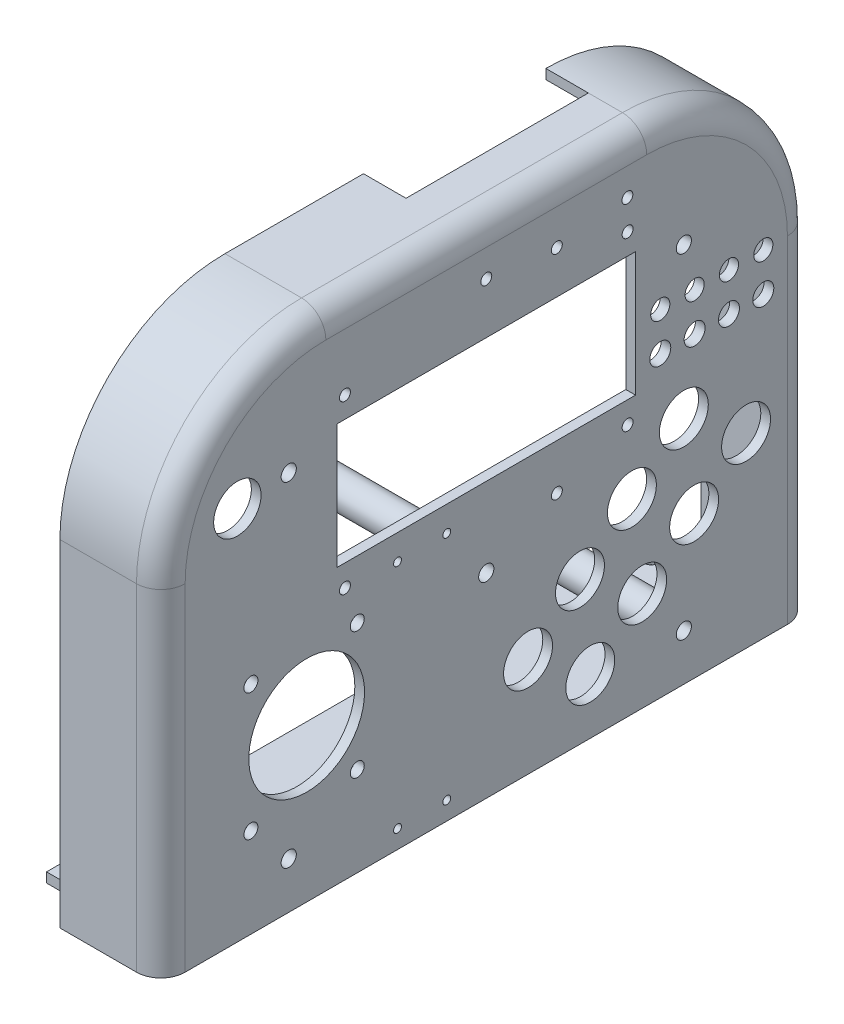
SolidWorks part; units mm, degrees
ref_plane "Front Plane" through (0, 0, 0) normal (0, 0, 1) x (1, 0, 0)
ref_plane "Top Plane" through (0, 0, 0) normal (0, 1, 0) x (1, 0, 0)
ref_plane "Right Plane" through (0, 0, 0) normal (1, 0, 0) x (0, 0, -1)
sketch "Sketch1" plane through (0, 0, 0) normal (1, 0, 0) x (0, 0, -1)
  line L0 (-107.09, -0.1) -> (107.09, -0.1) construction
  line L1 (-49.1, -20.45) -> (49.1, -20.45)
  line L2 (-49.1, -20.45) -> (-49.1, 20.45)
  line L3 (-49.1, 20.45) -> (49.1, 20.45)
  line L4 (49.1, -20.45) -> (49.1, 20.45)
  line L5 (-49.1, -20.45) -> (49.1, 20.45) construction
  line L6 (-49.1, 20.45) -> (49.1, -20.45) construction
  line L11 (-49.1, 29.95) -> (49.1, 29.95) construction
  line L12 (-49.1, 29.95) -> (-49.1, -30.15) construction
  line L13 (-49.1, -30.15) -> (49.1, -30.15) construction
  line L14 (49.1, 29.95) -> (49.1, -30.15) construction
  line L15 (-49.1, 20.45) -> (-82.6403, 20.45) construction
  line L16 (0, 0) -> (0, -0.1) construction
  line L17 (-46.5, -27.6) -> (46.5, -27.6) construction
  line L18 (-46.5, -27.6) -> (-46.5, 27.4) construction
  line L19 (-46.5, 27.4) -> (46.5, 27.4) construction
  line L20 (46.5, -27.6) -> (46.5, 27.4) construction
  line L21 (-46.5, -27.6) -> (46.5, 27.4) construction
  line L22 (-46.5, 27.4) -> (46.5, -27.6) construction
  line L23 (47.911, -49.4394) -> (85.4788, -49.4394) construction
  line L24 (65, -35.1) -> (85.4788, -49.4394) construction
  line L25 (47.911, -49.4394) -> (65, -35.1) construction
  line L26 (0, -0.1) -> (-71.6, -0.1) construction
  line L31 (0, -110.8) -> (0, 54.2) construction
  line L32 (-52.79, 54.2) -> (52.79, 54.2)
  line L33 (-59.95, -60.45) -> (-59.1, -60.45) construction
  line L34 (-42.45, -81.35) -> (-77.45, -81.35) construction
  line L35 (-42.45, -81.35) -> (-42.45, -39.55) construction
  line L36 (-42.45, -39.55) -> (-77.45, -39.55) construction
  line L37 (-77.45, -81.35) -> (-77.45, -39.55) construction
  line L38 (-42.45, -81.35) -> (-77.45, -39.55) construction
  line L39 (-42.45, -39.55) -> (-77.45, -81.35) construction
  line L40 (-107.09, -0.1) -> (-107.09, -110.8)
  line L41 (-107.09, -110.8) -> (107.09, -110.8)
  line L42 (107.09, -0.1) -> (107.09, -110.8)
  line L43 (0, -40.5) -> (0, -46.55) construction
  line L45 (-65, -95.5) -> (65, -95.5) construction
  line L46 (-65, -95.5) -> (-65, 14.5) construction
  line L47 (-65, 14.5) -> (65, 14.5) construction
  line L48 (65, -95.5) -> (65, 14.5) construction
  line L49 (-65, -95.5) -> (65, 14.5) construction
  line L50 (-65, 14.5) -> (65, -95.5) construction
  line L51 (46.42, 54.2) -> (46.42, 37.2) construction
  line L52 (0, 37.2) -> (46.42, 37.2) construction
  line L53 (23.21, 37.2) -> (23.21, -27.6) construction
  line L54 (-42.45, -81.35) -> (0, -81.35) construction
  line L56 (-29.2, -28.8) -> (-13, -28.8) construction
  line L58 (-29.2, -104.8) -> (-13, -104.8) construction
  line L59 (-29.2, -104.8) -> (-29.2, -28.8) construction
  line L60 (-29.2, -28.8) -> (-13, -28.8) construction
  line L61 (-13, -104.8) -> (-13, -28.8) construction
  line L62 (-29.2, -104.8) -> (-13, -28.8) construction
  line L63 (-29.2, -28.8) -> (-13, -104.8) construction
  line L65 (91.15, -3.25) -> (91.15, -9.25) construction
  circle A0 centre (46.5, 27.4) radius 1.8
  circle A1 centre (-46.5, -27.6) radius 1.8
  circle A2 centre (-46.5, 27.4) radius 1.8
  circle A3 centre (46.5, -27.6) radius 1.8
  circle A4 centre (57.25, -0.1) radius 3.15
  circle A5 centre (68.55, -0.1) radius 3.15
  circle A6 centre (79.85, -0.1) radius 3.15
  circle A7 centre (91.15, -0.1) radius 3.15
  circle A9 centre (46.5, 27.4) radius 2.55 construction
  circle A10 centre (46.5, -27.6) radius 2.55 construction
  circle A11 centre (65, -35.1) radius 8.05
  circle A12 centre (85.4788, -49.4394) radius 8.05
  circle A13 centre (68.3898, -63.7788) radius 8.05
  circle A14 centre (51.3007, -78.1182) radius 8.05
  circle A15 centre (34.2117, -92.4576) radius 8.05
  circle A16 centre (47.911, -49.4394) radius 8.05
  circle A17 centre (30.8219, -63.7788) radius 8.05
  circle A18 centre (13.7329, -78.1182) radius 8.05
  circle A25 centre (-77.45, -81.35) radius 2.3
  circle A26 centre (-42.45, -81.35) radius 2.3
  circle A27 centre (-42.45, -39.55) radius 2.3
  circle A28 centre (-77.45, -39.55) radius 2.3
  circle A29 centre (-59.1, -60.45) radius 19.05
  arc A30 (52.79, 54.2) -> (107.09, -0.1) centre (52.79, -0.1) cw
  arc A31 (-52.79, 54.2) -> (-107.09, -0.1) centre (-52.79, -0.1) ccw
  circle A37 centre (-65, -95.5) radius 2.5
  circle A38 centre (65, -95.5) radius 2.5
  circle A39 centre (65, 14.5) radius 2.5
  circle A40 centre (-65, 14.5) radius 2.5
  circle A41 centre (-81.9, 12.7) radius 7.8
  circle A43 centre (0, -46.55) radius 2.5
  circle A44 centre (46.42, 37.2) radius 1.8
  circle A45 centre (0, 37.2) radius 1.8
  circle A46 centre (23.21, 34.55) radius 1.8
  circle A47 centre (23.21, -35.45) radius 1.8
  circle A48 centre (-29.2, -28.8) radius 1.3
  circle A49 centre (-13, -28.8) radius 1.3
  circle A50 centre (-13, -104.8) radius 1.3
  circle A51 centre (-29.2, -104.8) radius 1.3
  circle A52 centre (91.15, -12.7) radius 3.45
  circle A53 centre (79.85, -12.7) radius 3.45
  circle A54 centre (68.55, -12.7) radius 3.45
  circle A55 centre (57.25, -12.7) radius 3.45
  point P1 (0, 0)
  point P11 (46.5, 27.4)
  point P12 (-46.5, -27.6)
  point P16 (-48.3, -27.6)
  point P17 (-46.5, -29.4)
  point P18 (48.3, 27.4)
  point P19 (46.5, 29.2)
  point P22 (-46.5, 29.2)
  point P23 (-48.3, 27.4)
  point P26 (46.5, -29.4)
  point P27 (48.3, -27.6)
  point P30 (54.1, -0.1)
  point P31 (60.4, -0.1)
  point P32 (57.25, 3.05)
  point P36 (65.4, -0.1)
  point P37 (71.7, -0.1)
  point P40 (76.7, -0.1)
  point P41 (83, -0.1)
  point P44 (88, -0.1)
  point P45 (88, -0.1)
  point P47 (-74.1, 12.7)
  point P48 (-64.1, -0.1)
  point P49 (-71.6, 7.4)
  point P52 (0, -0.1)
  point P67 (65, -35.1)
  point P86 (0, -0.1)
  point P92 (0, -28.3)
  point P96 (-59.95, -60.45)
  point P97 (-42.45, -39.55)
  point P98 (-77.45, -39.55)
  point P99 (-77.45, -81.35)
  point P100 (-42.45, -81.35)
  point P107 (0, -40.5)
  point P116 (-71.6, 7.4)
  point P119 (-74.1, 12.7)
  point P120 (-81.9, 20.5)
  point P123 (23.21, 37.2)
  point P124 (0, 37.2)
  point P125 (0, -28.3)
  point P127 (46.42, 37.2)
  point P134 (-21.225, -81.35)
  point P136 (-81.9, 4.9)
  point P141 (-21.1, -28.8)
  point P147 (-21.1, -66.8)
  point P155 (60.7, -12.7)
  point P156 (65.1, -12.7)
  point P157 (72, -12.7)
  point P158 (76.4, -12.7)
  point P159 (83.3, -12.7)
  point P160 (87.7, -12.7)
  point P161 (54.0776, -44.265)
  point P162 (65, -56.4773)
  point P163 (58.8333, -40.2744)
  point P164 (65, -43.15)
  point P167 (57.25, -9.25)
  point P168 (57.25, -3.25)
  dimension "D4" = 3.6
  dimension "D13" = 19.09
  dimension "D14" = 2
  dimension "D16" = 65
  dimension "D19" = 6.3
  dimension "D29" = 18.35
  dimension "D30" = 38.1
  dimension "D31" = 35
  dimension "D32" = 15.6
  dimension "D11" = 16.1
  dimension "D12" = 25
  dimension "D21" = 40
  dimension "D26" = 4.6
  dimension "D34" = 25
  dimension "D36" = 130
  dimension "D37" = 165
  dimension "D39" = 5
  dimension "D42" = 54.3
  dimension "D43" = 15.3
  dimension "D49" = 70
  dimension "D53" = 2.6
  dimension "D48" = 6.9
  dimension "D59" = 13.3273
  dimension "D1" = 98.2
  dimension "D2" = 40.9
  dimension "D5" = 55
  dimension "D6" = 93
  dimension "D7" = 60.1
  dimension "D8" = 98.2
  dimension "D9" = 9.7
  dimension "D10" = 0
  dimension "D15" = 4
  dimension "D17" = 35
  dimension "D18" = 40
  dimension "D20" = 5
  dimension "D22" = 10
  dimension "D23" = 5
  dimension "D24" = 5
  dimension "D25" = 5
  dimension "D27" = 35
  dimension "D28" = 41.8
  dimension "D33" = 25
  dimension "D35" = 33.5403
  dimension "D38" = 110
  dimension "D40" = 214.18
  dimension "D41" = 5
  dimension "D44" = 6.05
  dimension "D45" = 12.2
  dimension "D46" = 46.42
  dimension "D47" = 17
  dimension "D50" = 15
  dimension "D51" = 76
  dimension "D52" = 16.2
  dimension "D54" = 6
  dimension "D55" = 13
  dimension "D56" = 6.65
  dimension "D57" = 6.2082
  dimension "D58" = 6
extrude "Boss-Extrude1" add sketch "Sketch1" along normal blind 3.2
sketch "Sketch3" plane through (0, 0, 0) normal (-1, 0, 0) x (0, 0, 1)
  line L0 (-103.89, -0.1) -> (-103.89, -107.6)
  line L1 (-103.89, -107.6) -> (103.89, -107.6)
  line L2 (103.89, -107.6) -> (103.89, -0.1)
  line L3 (52.79, 51) -> (-52.79, 51)
  line L4 (-107.09, -0.1) -> (-107.09, -110.8)
  line L5 (-107.09, -110.8) -> (107.09, -110.8)
  line L6 (107.09, -110.8) -> (107.09, -0.1)
  line L7 (52.79, 54.2) -> (-52.79, 54.2)
  line L8 (-107.09, -0.1) -> (-107.09, -110.8)
  line L9 (-107.09, -110.8) -> (107.09, -110.8)
  line L10 (107.09, -110.8) -> (107.09, -0.1)
  line L11 (52.79, 54.2) -> (-52.79, 54.2)
  arc A0 (103.89, -0.1) -> (52.79, 51) centre (52.79, -0.1) ccw
  arc A1 (-52.79, 51) -> (-103.89, -0.1) centre (-52.79, -0.1) ccw
  arc A2 (-52.79, 54.2) -> (-107.09, -0.1) centre (-52.79, -0.1) ccw
  arc A3 (107.09, -0.1) -> (52.79, 54.2) centre (52.79, -0.1) ccw
  arc A4 (-52.79, 54.2) -> (-107.09, -0.1) centre (-52.79, -0.1) ccw
  arc A5 (107.09, -0.1) -> (52.79, 54.2) centre (52.79, -0.1) ccw
  dimension "D3" = 207.78
  dimension "D4" = 158.6
  dimension "D1" = 0
  dimension "D2" = 3.2
extrude "Boss-Extrude2" add sketch "Sketch3" along normal blind 30
fillet "Fillet1" radius 4.8 5 edges at (0, -53.85, -103.89) (0, 36.0332, -88.9232) (0, 51, 0) (0, 36.0332, 88.9232) (0, -53.85, 103.89)
fillet "Fillet2" radius 8 5 edges at (3.2, -55.45, -107.09) (3.2, 38.2959, -91.1859) (3.2, 54.2, 0) (3.2, 38.2959, 91.1859) (3.2, -55.45, 107.09)
sketch "Sketch6" plane through (0, 0, 0) normal (-1, 0, 0) x (0, 0, 1)
  line L0 (-65, -95.5) -> (65, 14.5) construction
  line L1 (65, -95.5) -> (-65, 14.5) construction
  line L2 (0, -40.5) -> (0, -46.55) construction
  circle A4 centre (65, 14.5) radius 5.25
  circle A5 centre (65, 14.5) radius 2.5
  circle A8 centre (-65, 14.5) radius 5.25
  circle A9 centre (-65, 14.5) radius 2.5
  circle A12 centre (-65, -95.5) radius 5.25
  circle A13 centre (-65, -95.5) radius 2.5
  circle A14 centre (65, -95.5) radius 5.25
  circle A15 centre (65, -95.5) radius 2.5
  circle A18 centre (0, -46.55) radius 2.5
  circle A19 centre (0, -46.55) radius 5.25
  point P2 (0, -40.5)
  point P4 (-65, 14.5)
  point P13 (0, -46.55)
  point P15 (65, 14.5)
  dimension "D10" = 10.5
  dimension "D9" = 5
extrude "Boss-Extrude3" add sketch "Sketch6" along normal blind 50
sketch "Sketch12" plane through (-30, 0, 0) normal (-1, 0, 0) x (0, 0, 1)
  line L0 (96.49, -107.6) -> (96.49, -110.8)
  line L1 (-96.49, -107.6) -> (-96.49, -110.8)
  line L2 (107.09, -110.8) -> (96.49, -110.8) construction
  line L3 (-96.49, -107.6) -> (96.49, -107.6)
  line L4 (-96.49, -110.8) -> (-107.09, -110.8) construction
  line L13 (52.79, 54.2) -> (-52.79, 54.2)
  line L14 (-107.09, -0.1) -> (-107.09, -110.8)
  line L15 (-107.09, -110.8) -> (107.09, -110.8)
  line L16 (107.09, -110.8) -> (107.09, -0.1)
  line L26 (-107.09, -0.1) -> (-107.09, -110.8) construction
  line L27 (-96.49, -110.8) -> (96.49, -110.8)
  line L28 (107.09, -110.8) -> (107.09, -0.1) construction
  arc A4 (-52.79, 54.2) -> (-107.09, -0.1) centre (-52.79, -0.1) ccw
  arc A5 (107.09, -0.1) -> (52.79, 54.2) centre (52.79, -0.1) ccw
  point P15 (-96.49, -107.6)
  point P16 (96.49, -107.6)
  dimension "D2" = 10.6
  dimension "D3" = 10.6
  dimension "D4" = 3.2
  dimension "D1" = 0
extrude "Boss-Extrude7" add sketch "Sketch12" along normal blind 15
sketch "Sketch8" plane through (0, -110.8, 0) normal (0, -1, 0) x (1, 0, 0)
  line L0 (3.2, 99.09) -> (-30, 99.09) construction
  line L1 (-30, -107.09) -> (-30, -96.49) construction
  line L2 (-4.8, 107.09) -> (-4.8, 47.09) construction
  line L3 (-6, 92.09) -> (-24.6, 92.09) construction
  line L5 (-34.6, 92.09) -> (-14.6, 92.09) construction
  line L6 (3.2, -99.09) -> (-30, -99.09) construction
  line L7 (-4.8, -107.09) -> (-4.8, -47.09) construction
  line L8 (-6, -92.09) -> (-24.6, -92.09) construction
  line L9 (-4.8, -107.09) -> (-30, -107.09) construction
  line L10 (-14.6, -92.09) -> (-34.6, -92.09) construction
  line L11 (-4.8, 107.09) -> (-30, 107.09) construction
  circle A0 centre (-14.6, 92.09) radius 2.3
  circle A1 centre (-34.6, 92.09) radius 2.3
  circle A2 centre (-14.6, -92.09) radius 2.3
  circle A3 centre (-34.6, -92.09) radius 2.3
  point P8 (-4.8, 77.1)
  point P9 (-13.4, 99.09)
  point P16 (-24.6, 92.09)
  point P24 (-4.8, -77.09)
  point P25 (-13.4, -99.09)
  point P32 (-24.6, -92.09)
  dimension "D3" = 4.6
  dimension "D6" = 4.6
  dimension "D1" = 60
  dimension "D2" = 20
  dimension "D4" = 60
  dimension "D5" = 20
  dimension "D7" = 15
  dimension "D8" = 15
  dimension "D9" = 19.8
  dimension "D10" = 19.8
extrude "Cut-Extrude2" cut sketch "Sketch8" against normal blind 10
sketch "Sketch19" plane through (0, 54.2, 0) normal (0, 1, 0) x (1, 0, 0)
  line L0 (-30, 52.79) -> (-16, 52.79)
  line L1 (-4.8, 52.79) -> (-30, 52.79) construction
  line L2 (-16, 52.79) -> (-16, -7.21)
  line L3 (-16, -7.21) -> (-30, -7.21)
  line L4 (-30, -52.79) -> (-30, 52.79) construction
  line L5 (-30, -7.21) -> (-30, 52.79)
  dimension "D1" = 14
  dimension "D2" = 60
extrude "Cut-Extrude7" cut sketch "Sketch19" against normal blind 10
